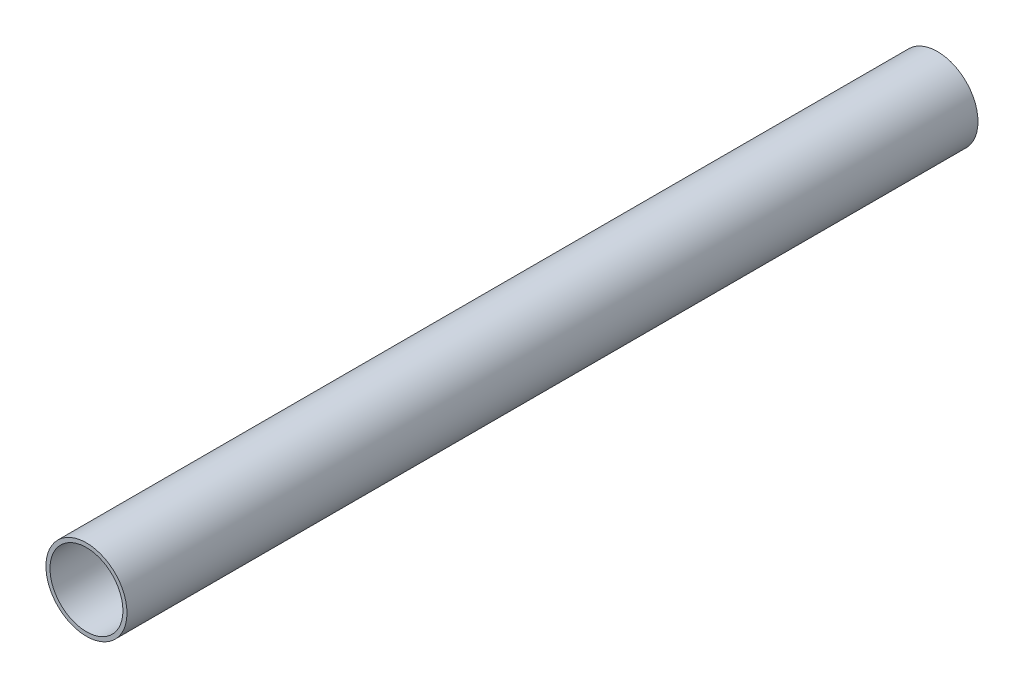
SolidWorks part; units mm, degrees
material "Manual Density from Real Component Longherone"
ref_plane "Piano frontale" through (0, 0, 0) normal (0, 0, 1) x (1, 0, 0)
ref_plane "Piano superiore" through (0, 0, 0) normal (0, 1, 0) x (1, 0, 0)
ref_plane "Piano destro" through (0, 0, 0) normal (1, 0, 0) x (0, 0, -1)
sketch "Schizzo1" plane through (0, 0, 0) normal (0, 0, 1) x (1, 0, 0)
  circle A0 centre (0, 0) radius 9
  circle A1 centre (0, 0) radius 10
  dimension "D1" = 18
  dimension "D2" = 20
extrude "Estrusione-Estrusione1" add sketch "Schizzo1" along normal blind 210
